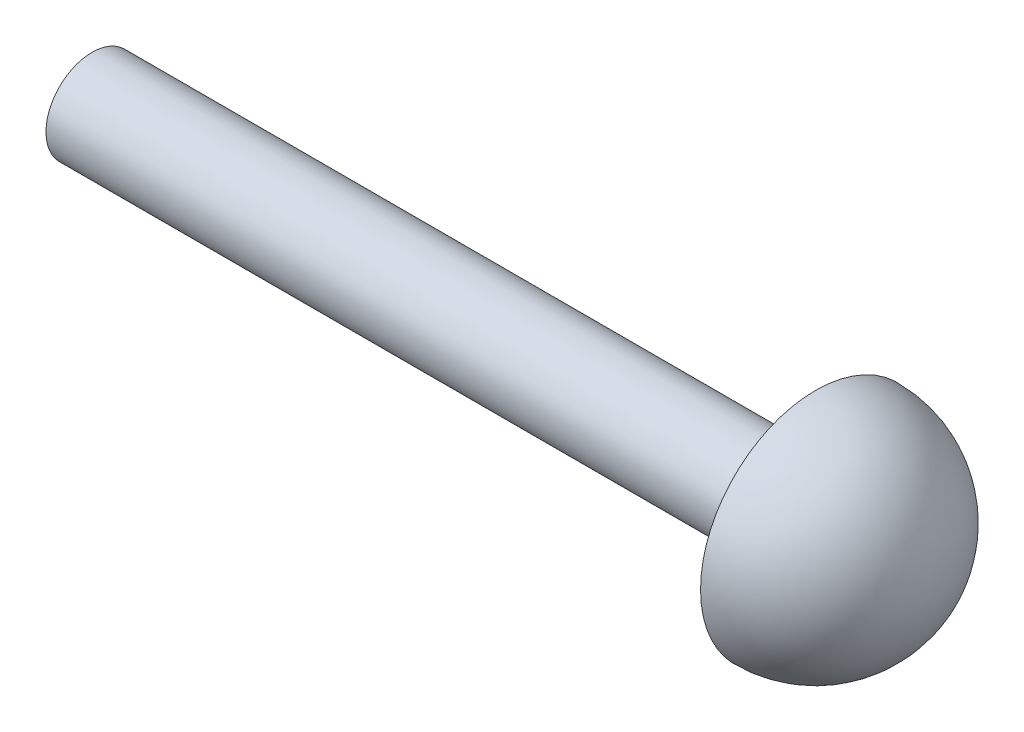
SolidWorks part; units mm, degrees
ref_plane "Front Plane" through (0, 0, 0) normal (0, 0, 1) x (1, 0, 0)
ref_plane "Top Plane" through (0, 0, 0) normal (0, 1, 0) x (1, 0, 0)
ref_plane "Right Plane" through (0, 0, 0) normal (1, 0, 0) x (0, 0, -1)
sketch "Sketch1" plane through (0, 0, 0) normal (0, 0, 1) x (1, 0, 0)
  line L0 (0, 5) -> (0, 2)
  line L1 (-31.4498, 2) -> (0, 2)
  line L2 (-31.4498, 2) -> (-31.4498, 0)
  line L3 (-31.4498, 0) -> (0, 0)
  line L4 (0, 0) -> (5, 0)
  arc A0 (5, 0) -> (0, 5) centre (0, 0) ccw
  dimension "D2" = 5
  dimension "D1" = 31.4498
  dimension "D3" = 2
revolve "Revolve1" add sketch "Sketch1" angle 360 about L3
